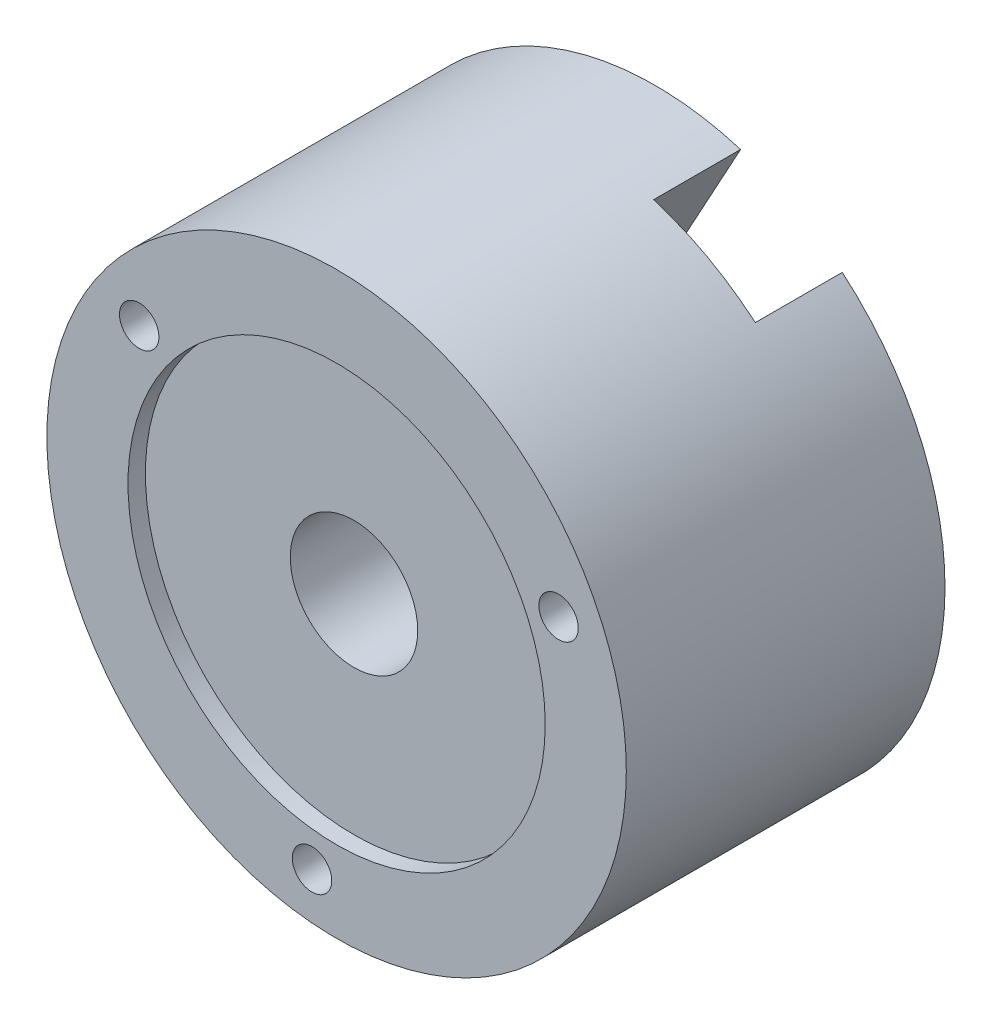
SolidWorks part; units mm, degrees
material "AISI 304"
ref_plane "Front Plane" through (0, 0, 0) normal (0, 0, 1) x (1, 0, 0)
ref_plane "Top Plane" through (0, 0, 0) normal (0, 1, 0) x (1, 0, 0)
ref_plane "Right Plane" through (0, 0, 0) normal (1, 0, 0) x (0, 0, -1)
sketch "Sketch1" plane through (0, 0, 0) normal (0, 0, 1) x (1, 0, 0)
  circle A0 centre (0, 0) radius 50
  dimension "D1" = 100
extrude "Boss-Extrude1" add sketch "Sketch1" along normal blind 55
sketch "Sketch2" plane through (0, 0, 55) normal (0, 0, 1) x (1, 0, 0)
  circle A0 centre (0, 0) radius 36
  dimension "D1" = 72
extrude "Cut-Extrude1" cut sketch "Sketch2" against normal blind 3
sketch "Sketch3" plane through (0, 0, 52) normal (0, 0, 1) x (1, 0, 0)
  circle A0 centre (0, 0) radius 11
  dimension "D1" = 22
extrude "Cut-Extrude2" cut sketch "Sketch3" against normal up to next
hole_wizard "M8x1.25 Tapped Hole1" positions "Sketch4" profile "Sketch6" tap size "M8x1.25" standard "ANSI Metric"
sketch "Sketch4" plane through (0, 0, 55) normal (0, 0, 1) x (1, 0, 0)
  point P8 (-34.0687, 24.5627)
  point P23 (38.3062, 17.223)
  point P24 (-4.2376, -41.7857)
  point P25 (0, 0)
  point P26 (0, 0)
  point P27 (0, 0)
  dimension "D2" = 3
sketch "Sketch6" plane through (-34.0687, 24.5627, 55) normal (1, 0, 0) x (0, -1, 0)
  line L0 (0, 0) -> (0, 12.2929)
  line L1 (0, 12.2929) -> (3.4, 10.25)
  line L2 (3.4, 10.25) -> (3.4, 0)
  line L5 (3.4, 0) -> (0, 0)
  line L10 (0, 12.2929) -> (-3.4, 10.25) construction
  line L11 (0, -6.35) -> (0, 107.95) construction
  dimension "Tap Drill Dia." = 6.8
  dimension "Tap Drill Depth" = 10.25
  dimension "Drill Angle" = 118
cosmetic thread "Hole Thread1" parameters "D1"=4, "D2"=8
cosmetic thread "Hole Thread2" parameters "D1"=4, "D2"=8
cosmetic thread "Hole Thread3" parameters "D1"=4, "D2"=8
sketch "Sketch7" plane through (0, 0, 0) normal (0, 0, -1) x (-1, 0, 0)
  line L4 (-56.7308, 82.9555) -> (-11.5438, 0.2707)
  line L5 (-56.7308, 82.9555) -> (-39.1805, 92.5467)
  line L7 (-39.1805, 92.5467) -> (6.0064, 9.8619)
  line L8 (-56.7308, 82.9555) -> (-23.9778, 43.8755) construction
  line L9 (-23.9778, 43.8755) -> (-39.1805, 92.5467) construction
  line L10 (100.207, 7.6525) -> (6.0064, 9.8619)
  line L11 (100.207, 7.6525) -> (99.738, -12.342)
  line L13 (99.738, -12.342) -> (5.5374, -10.1326)
  line L14 (100.207, 7.6525) -> (49.9863, -1.1724) construction
  line L15 (49.9863, -1.1724) -> (99.738, -12.342) construction
  line L16 (-43.4762, -90.6081) -> (5.5374, -10.1326)
  line L17 (-43.4762, -90.6081) -> (-60.5575, -80.2047)
  line L19 (-60.5575, -80.2047) -> (-11.5438, 0.2707)
  line L20 (-43.4762, -90.6081) -> (-26.0084, -42.7032) construction
  line L27 (-26.0084, -42.7032) -> (-60.5575, -80.2047) construction
  line L28 (4.9642, -9.0837) -> (4.0305, -10.0973) construction
  point P1 (-23.9778, 43.8755)
  point P10 (49.9863, -1.1724)
  point P15 (-26.0084, -42.7032)
  point P20 (0, 0)
  dimension "D1" = 20
  dimension "D2" = 3
extrude "Cut-Extrude3" cut sketch "Sketch7" against normal blind 15
